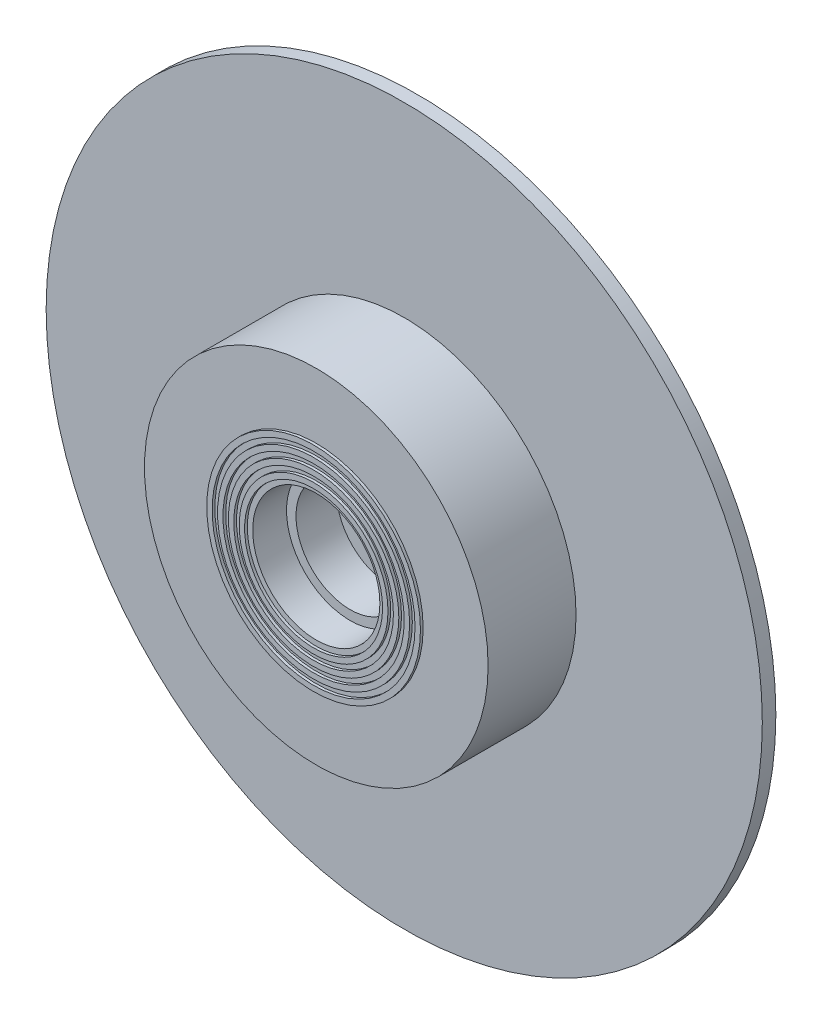
SolidWorks part; units mm, degrees
material "AISI 316 Annealed Stainless Steel Bar (SS)"
ref_plane "Front Plane" through (0, 0, 0) normal (1, 0, 0) x (0, 1, 0)
ref_plane "Top Plane" through (0, 0, 0) normal (0, 0, 1) x (0, 1, 0)
ref_plane "Right Plane" through (0, 0, 0) normal (0, 1, 0) x (-1, 0, 0)
sketch "Sketch1" plane through (0, 0, 0) normal (1, 0, 0) x (0, 1, 0)
  line L0 (-132.334, 0) -> (-60.5, 0)
  line L1 (-12.1, 5) -> (-12.1, 10)
  line L2 (-12.1, 10) -> (-20, 10)
  line L3 (-20, 10) -> (-20, 25)
  line L4 (-20, 25) -> (-23.5, 25)
  line L5 (-23.5, 25) -> (-23.5, 37.5)
  line L6 (-23.5, 37.5) -> (-25.5, 37.5)
  line L7 (-25.5, 37.5) -> (-25.5, 38.5)
  line L8 (-25.5, 38.5) -> (-27.5, 38.5)
  line L9 (-27.5, 38.5) -> (-27.5, 37.5)
  line L10 (-27.5, 37.5) -> (-29.5, 37.5)
  line L11 (-29.5, 37.5) -> (-29.5, 38.5)
  line L12 (-29.5, 38.5) -> (-31.5, 38.5)
  line L13 (-31.5, 38.5) -> (-31.5, 37.5)
  line L15 (-63.5, 37.5) -> (-63.5, 5)
  line L16 (-132.334, 0) -> (-132.334, 5)
  line L17 (-132.334, 5) -> (-63.5, 5)
  line L18 (0, 0) -> (0, 1465.0942) construction
  line L19 (-31.5, 37.5) -> (-33.5, 37.5)
  line L20 (-33.5, 37.5) -> (-33.5, 38.5)
  line L21 (-33.5, 38.5) -> (-35.5, 38.5)
  line L22 (-35.5, 38.5) -> (-35.5, 37.5)
  line L23 (-35.5, 37.5) -> (-37.5, 37.5)
  line L24 (-37.5, 37.5) -> (-37.5, 38.5)
  line L25 (-37.5, 38.5) -> (-39.5, 38.5)
  line L26 (-39.5, 38.5) -> (-39.5, 37.5)
  line L27 (-39.5, 37.5) -> (-63.5, 37.5)
  line L28 (-60.5, 0) -> (-60.5, 32.5)
  line L29 (-60.5, 32.5) -> (-28.5, 32.5)
  line L30 (-28.5, 32.5) -> (-28.5, 5)
  line L31 (-28.5, 5) -> (-12.1, 5)
  dimension "D1" = 132.334
  dimension "D2" = 23.5
  dimension "D3" = 12.5
  dimension "D4" = 2
  dimension "D5" = 1
  dimension "D6" = 63.5
  dimension "D7" = 2
  dimension "D8" = 5
  dimension "D9" = 20
  dimension "D10" = 12.1
  dimension "D11" = 15
  dimension "D12" = 5
  dimension "D13" = 3
  dimension "D14" = 5
  dimension "D15" = 5
  dimension "D16" = 5
ref_axis "Axis1" through (0, 0, 1538.3489) along (0, 0, -1)
revolve "Revolve1" add sketch "Sketch1" angle 360 about axis through (0, 0, 1538.3489) along (0, 0, -1)
